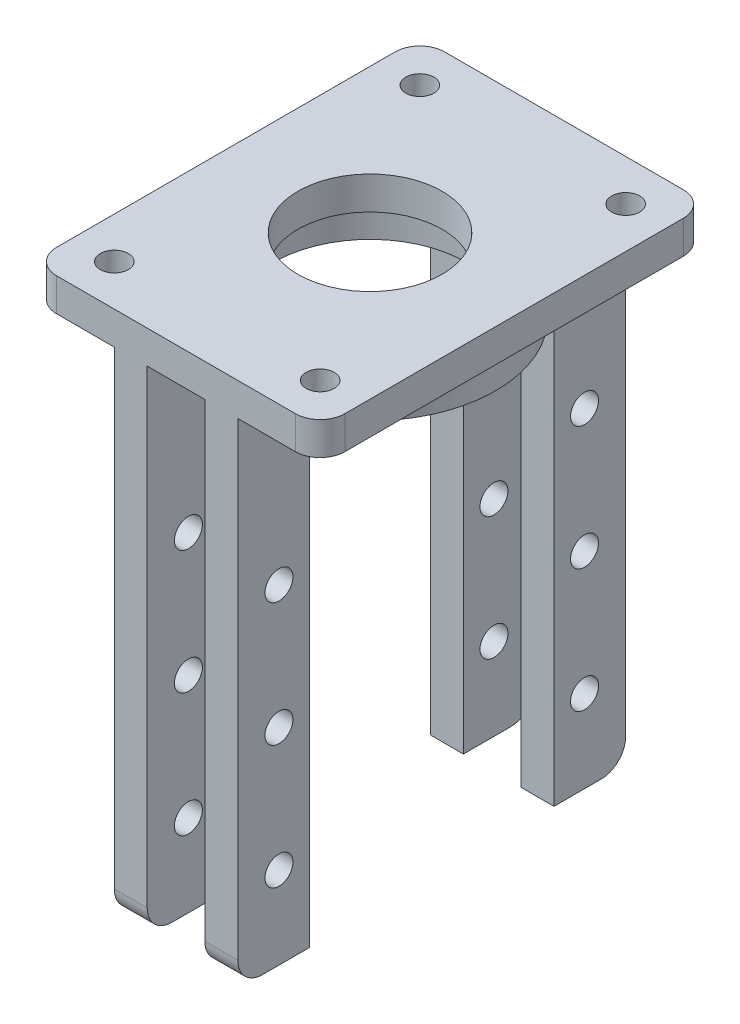
SolidWorks part; units mm, degrees
ref_plane "Front Plane" through (0, 0, 0) normal (0, 0, 1) x (1, 0, 0)
ref_plane "Top Plane" through (0, 0, 0) normal (0, 1, 0) x (1, 0, 0)
ref_plane "Right Plane" through (0, 0, 0) normal (1, 0, 0) x (0, 0, -1)
sketch "Sketch1" plane through (0, 0, 0) normal (0, 1, 0) x (1, 0, 0)
  line L1 (-17.5, 23.555) -> (17.5, 23.555)
  line L2 (-17.5, 23.555) -> (-17.5, -23.555)
  line L3 (-17.5, -23.555) -> (17.5, -23.555)
  line L4 (17.5, 23.555) -> (17.5, -23.555)
  line L5 (0, -23.555) -> (0, 23.555) construction
  line L6 (-17.5, 0) -> (17.5, 0) construction
  point P4 (0, 0)
  point P316 (0, 0)
  dimension "D1" = 47.11
  dimension "D2" = 35
extrude "Boss-Extrude1" add sketch "Sketch1" along normal blind 4
sketch "Sketch2" plane through (0, 0, 0) normal (0, -1, 0) x (1, 0, 0)
  circle A0 centre (0, 0) radius 11.75
  circle A1 centre (0, 0) radius 15.25
  dimension "D1" = 23.5
  dimension "D2" = 3.5
extrude "Boss-Extrude2" add sketch "Sketch2" along normal blind 5
sketch "Sketch3" plane through (0, 0, 0) normal (0, -1, 0) x (-1, 0, 0)
  line L0 (17.5, 0) -> (-17.5, 0) construction
  line L3 (17.5, 23.555) -> (17.5, -23.555) construction
  line L4 (-17.5, -23.555) -> (-17.5, 23.555) construction
  line L5 (0, 23.555) -> (0, -23.555) construction
  line L6 (7.5, 23.555) -> (7.5, 13.2783)
  line L7 (7.5, 23.555) -> (3.5, 23.555)
  line L8 (3.5, 23.555) -> (3.5, 14.8429)
  line L9 (-7.5, 23.555) -> (-3.5, 23.555)
  line L10 (-7.5, 23.555) -> (-7.5, 13.2783)
  line L11 (-3.5, 23.555) -> (-3.5, 14.8429)
  line L12 (-7.5, -23.555) -> (-7.5, -13.2783)
  line L13 (-7.5, -23.555) -> (-3.5, -23.555)
  line L14 (-3.5, -23.555) -> (-3.5, -14.8429)
  line L15 (3.5, -23.555) -> (3.5, -14.8429)
  line L16 (7.5, -23.555) -> (3.5, -23.555)
  line L17 (7.5, -23.555) -> (7.5, -13.2783)
  arc A1 (7.5, 13.2783) -> (3.5, 14.8429) centre (0, 0) ccw
  arc A2 (-3.5, 14.8429) -> (-7.5, 13.2783) centre (0, 0) ccw
  arc A3 (-7.5, -13.2783) -> (-3.5, -14.8429) centre (0, 0) ccw
  arc A4 (3.5, -14.8429) -> (7.5, -13.2783) centre (0, 0) ccw
  point P8 (0, 0)
  dimension "D2" = 4
  dimension "D1" = 47.11
  dimension "D3" = 7
extrude "Boss-Extrude3" add sketch "Sketch3" along normal blind 60
sketch "Sketch5" plane through (0, -60, 0) normal (0, -1, 0) x (1, 0, 0)
  line L0 (-3.5, 14.8429) -> (-7.5, 14.8429)
  line L1 (-7.5, 23.555) -> (-7.5, 13.2783) construction
  line L2 (-7.5, 14.8429) -> (-7.5, 13.2783)
  line L3 (0, 0) -> (0, 11.75) construction
  line L4 (0, 0) -> (11.75, 0) construction
  line L5 (3.5, 14.8429) -> (7.5, 14.8429)
  line L6 (7.5, 14.8429) -> (7.5, 13.2783)
  line L7 (7.5, -14.8429) -> (7.5, -13.2783)
  line L8 (3.5, -14.8429) -> (7.5, -14.8429)
  line L9 (-3.5, -14.8429) -> (-7.5, -14.8429)
  line L10 (-7.5, -14.8429) -> (-7.5, -13.2783)
  arc A0 (-7.5, -13.2783) -> (-3.5, -14.8429) centre (0, 0) ccw
  circle A1 centre (0, 0) radius 11.75 construction
  circle A2 centre (0, 0) radius 11.75 construction
  arc A3 (3.5, -14.8429) -> (7.5, -13.2783) centre (0, 0) ccw
  arc A4 (-3.5, 14.8429) -> (-7.5, 13.2783) centre (0, 0) ccw
  arc M10 (3.5, 14.8429) -> (7.5, 13.2783) centre (0, 0) cw
  line M11 (7.5, 13.2783) -> (7.5, 23.555)
extrude "Cut-Extrude1" cut sketch "Sketch5" against normal up to surface (55 mm away) contours A0 L10 L9 | L5 M10 M11 | A3 L7 L8 | L0 L2 A4 up to face at (0, -5, 0)
sketch "Sketch6" plane through (7.5, 0, 0) normal (1, 0, 0) x (0, 0, -1)
  line L0 (0, 0) -> (0, -76.2988) construction
  line L1 (-23.555, 0) -> (23.555, 0) construction
  line L2 (-18.555, -35) -> (18.555, -35) construction
  line L3 (-14.8429, -60) -> (-23.555, -60) construction
  circle A0 centre (-18.555, -35) radius 1.7
  circle A1 centre (-18.555, -20) radius 1.7
  circle A2 centre (-18.555, -50) radius 1.7
  circle A3 centre (18.555, -50) radius 1.7
  circle A4 centre (18.555, -35) radius 1.7
  circle A5 centre (18.555, -20) radius 1.7
  point P6 (0, -35)
  dimension "D2" = 3.4
  dimension "D1" = 37.11
  dimension "D4" = 10
  dimension "D3" = 2
extrude "Cut-Extrude2" cut sketch "Sketch6" against normal blind 60
sketch "Sketch7" plane through (0, 4, 0) normal (0, 1, 0) x (1, 0, 0)
  circle A0 centre (0, 0) radius 8.75
  dimension "D1" = 17.5
extrude "Cut-Extrude3" cut sketch "Sketch7" against normal blind 60
fillet "Fillet2" radius 3 4 edges at (5.5, -5, -14.8429) (-5.5, -5, -14.8429) (-5.5, -5, 14.8429) (5.5, -5, 14.8429)
fillet "Fillet3" radius 3 4 edges at (-5.5, -60, -23.555) (5.5, -60, -23.555) (-5.5, -60, 23.555) (5.5, -60, 23.555)
sketch "Sketch10" plane through (0, 4, 0) normal (0, 1, 0) x (1, 0, 0)
  line L0 (0, 23.555) -> (0, -23.555) construction
  line L1 (17.5, 23.555) -> (-17.5, 23.555) construction
  line L2 (-17.5, -23.555) -> (17.5, -23.555) construction
  line L3 (-17.5, 0) -> (17.5, 0) construction
  line L4 (-17.5, 23.555) -> (-17.5, -23.555) construction
  line L5 (17.5, -23.555) -> (17.5, 23.555) construction
  circle A0 centre (-12.5, 18.555) radius 1.7
  circle A1 centre (12.5, 18.555) radius 1.7
  circle A2 centre (12.5, -18.555) radius 1.7
  circle A3 centre (-12.5, -18.555) radius 1.7
  point P14 (-11.8822, 18.6943)
  dimension "D1" = 3.4
  dimension "D2" = 5
  dimension "D3" = 5
extrude "Cut-Extrude4" cut sketch "Sketch10" against normal through all
fillet "Fillet4" radius 3 4 edges at (17.5, 2, 23.555) (17.5, 2, -23.555) (-17.5, 2, -23.555) (-17.5, 2, 23.555)
